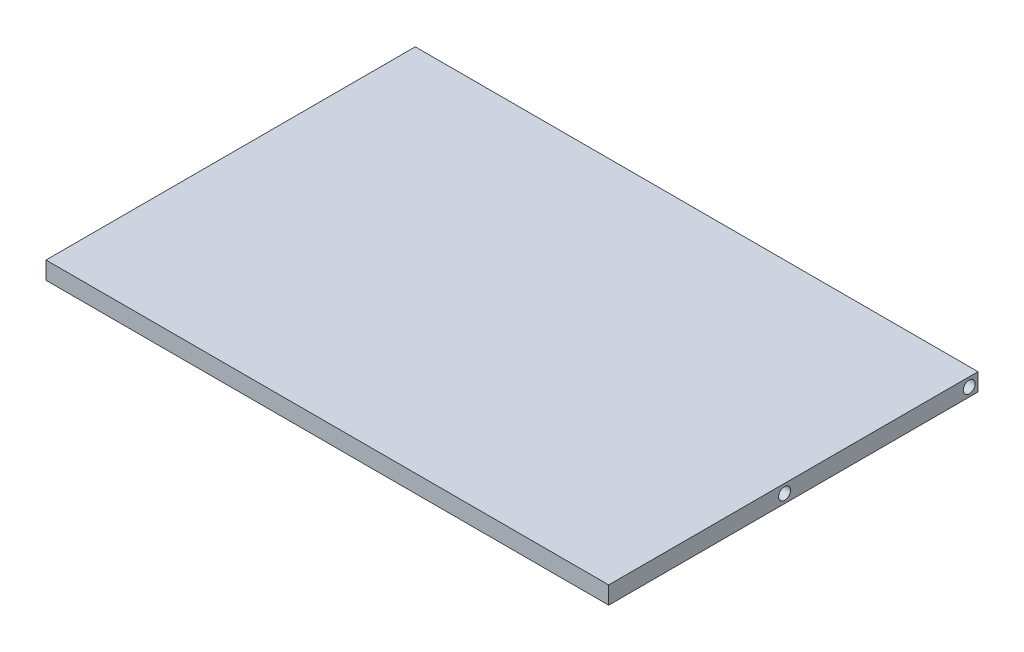
SolidWorks part; units mm, degrees
material "ABS PC"
ref_plane "前视基准面" through (0, 0, 0) normal (0, 0, 1) x (1, 0, 0)
ref_plane "上视基准面" through (0, 0, 0) normal (0, 1, 0) x (1, 0, 0)
ref_plane "右视基准面" through (0, 0, 0) normal (1, 0, 0) x (0, 0, -1)
other "Configuration Table"
sketch "草图1" plane through (0, 0, 0) normal (0, 1, 0) x (1, 0, 0)
  line L1 (-80, 52.5) -> (80, 52.5)
  line L2 (-80, 52.5) -> (-80, -52.5)
  line L3 (-80, -52.5) -> (80, -52.5)
  line L4 (80, 52.5) -> (80, -52.5)
  line L5 (-80, 52.5) -> (80, -52.5) construction
  line L6 (-80, -52.5) -> (80, 52.5) construction
  point P0 (0, 0)
  dimension "D1" = 160
  dimension "D2" = 105
extrude "凸台-拉伸1" add sketch "草图1" along normal blind 5
sketch "草图2" plane through (80, 0, 0) normal (1, 0, 0) x (0, 0, -1)
  circle A0 centre (-2.5, 2.5) radius 1.7
extrude "切除-拉伸1" cut sketch "草图2" against normal blind 200 contours A0
sketch "草图3" plane through (80, 0, 0) normal (1, 0, 0) x (0, 0, -1)
  circle A0 centre (50, 2.5) radius 1.7
extrude "切除-拉伸2" cut sketch "草图3" against normal blind 200 contours A0
